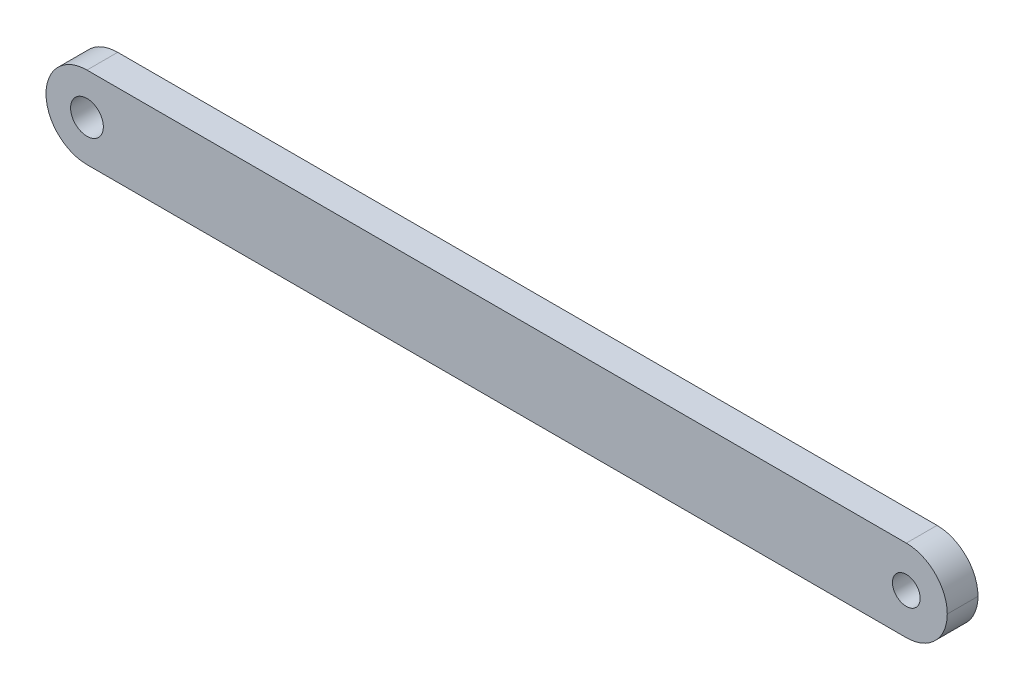
SolidWorks part; units mm, degrees
ref_plane "前视基准面" through (0, 0, 0) normal (0, 0, 1) x (1, 0, 0)
ref_plane "上视基准面" through (0, 0, 0) normal (0, 1, 0) x (1, 0, 0)
ref_plane "右视基准面" through (0, 0, 0) normal (1, 0, 0) x (0, 0, -1)
ref_plane "基准面4" through (0, 0, 0) normal (0, 0, -1) x (-1, 0, 0)
sketch "草图1" plane through (0, 0, 0) normal (0, 0, -1) x (-1, 0, 0)
  line L0 (-55.8602, 0) -> (24.1383, 0)
  line L1 (24.1383, 7.999) -> (-55.8602, 7.999)
  arc A0 (-55.8602, 7.999) -> (-59.8602, 4) centre (-55.8602, 3.999) ccw
  arc A1 (-59.8602, 4) -> (-55.8602, 0) centre (-55.8602, 4) ccw
  arc A2 (24.1383, 0) -> (28.1383, 3.999) centre (24.1383, 4) ccw
  arc A3 (28.1383, 3.999) -> (24.1383, 7.999) centre (24.1383, 3.999) ccw
  circle A4 centre (24.1388, 3.9985) radius 1.354
  circle A5 centre (-55.8597, 3.9995) radius 1.354
extrude "凸台-拉伸1" add sketch "草图1" against normal blind 3
sketch "草图2" plane through (0, 0, 3) normal (0, 0, 1) x (1, 0, 0)
  circle A0 centre (-24.1388, 3.9985) radius 1.6
  dimension "D1" = 3.2
extrude "切除-拉伸1" cut sketch "草图2" against normal through all
